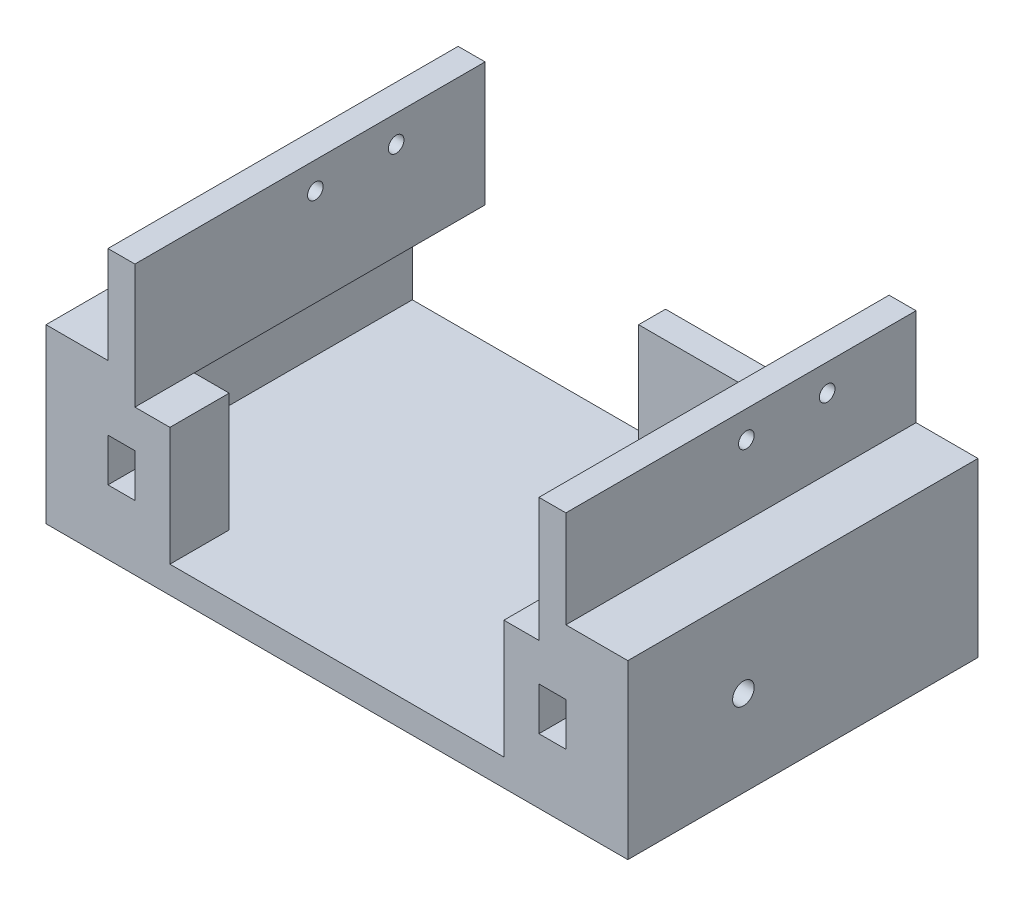
SolidWorks part; units mm, degrees
ref_plane "前基準面" through (0, 0, 0) normal (0, 0, 1) x (1, 0, 0)
ref_plane "上基準面" through (0, 0, 0) normal (0, 1, 0) x (1, 0, 0)
ref_plane "右基準面" through (0, 0, 0) normal (1, 0, 0) x (0, 0, -1)
sketch "草圖1" plane through (0, 0, 0) normal (0, 0, 1) x (1, 0, 0)
  line L0 (-26.3644, 0.7783) -> (-21.3644, 0.7783)
  line L1 (-21.3644, 0.7783) -> (-21.3644, -22.2217)
  line L2 (-21.3644, -22.2217) -> (-34.8644, -22.2217)
  line L3 (-34.8644, -22.2217) -> (-34.8644, -44.2217)
  line L4 (-34.8644, -44.2217) -> (67.1356, -44.2217)
  line L5 (67.1356, -44.2217) -> (67.1356, -22.2217)
  line L6 (67.1356, -22.2217) -> (53.6356, -22.2217)
  line L7 (53.6356, -22.2217) -> (53.6356, 0.7783)
  line L8 (53.6356, 0.7783) -> (58.6356, 0.7783)
  line L9 (58.6356, 0.7783) -> (58.6356, -17.2217)
  line L10 (58.6356, -17.2217) -> (70.1356, -17.2217)
  line L11 (70.1356, -17.2217) -> (70.1356, -49.2217)
  line L12 (70.1356, -49.2217) -> (-37.8644, -49.2217)
  line L13 (-37.8644, -49.2217) -> (-37.8644, -17.2217)
  line L14 (-37.8644, -17.2217) -> (-26.3644, -17.2217)
  line L15 (-26.3644, -17.2217) -> (-26.3644, 0.7783)
  dimension "D1" = 5
  dimension "D2" = 3
  dimension "D3" = 3
  dimension "D4" = 5
  dimension "D5" = 5
  dimension "D6" = 22
  dimension "D7" = 22
  dimension "D8" = 5
  dimension "D9" = 5
  dimension "D10" = 102
  dimension "D11" = 75
  dimension "D12" = 13.5
  dimension "D13" = 45
  dimension "D14" = 45
extrude "填料-伸長1" add sketch "草圖1" along normal blind 65
sketch "草圖3" plane through (-37.8644, 0, 0) normal (-1, 0, 0) x (0, 0, 1)
  line L0 (65, -17.2217) -> (0, -17.2217) construction
  circle A0 centre (43.5457, -33.2217) radius 2
  dimension "D2" = 4
  dimension "D1" = 16
extrude "除料-伸長2" cut sketch "草圖3" against normal through all contours A0
sketch "草圖4" plane through (0, 0, 0) normal (0, 0, -1) x (-1, 0, 0)
  line L0 (-67.1356, -44.2217) -> (34.8644, -44.2217) construction
  line L1 (-42.1356, -44.2217) -> (-12.1356, -44.2217)
  line L2 (-42.1356, -44.2217) -> (-42.1356, -22.2217)
  line L3 (-42.1356, -22.2217) -> (-12.1356, -22.2217)
  line L4 (-12.1356, -44.2217) -> (-12.1356, -22.2217)
  line L5 (-67.1356, -22.2217) -> (-67.1356, -44.2217) construction
  dimension "D1" = 30
  dimension "D2" = 25
  dimension "D3" = 22
extrude "填料-伸長2" add sketch "草圖4" against normal blind 5
sketch "草圖9" plane through (-21.3644, 0, 0) normal (1, 0, 0) x (0, 0, -1)
  circle A0 centre (-31.5, -4.2217) radius 1.45
  circle A1 centre (-16.5, -4.2217) radius 1.45
extrude "除料-伸長4" cut sketch "草圖9" against normal through all and the other way through all
sketch "草圖10" plane through (0, 0, 65) normal (0, 0, 1) x (1, 0, 0)
  line L1 (-34.8644, -44.2217) -> (-14.8644, -44.2217)
  line L2 (-34.8644, -44.2217) -> (-34.8644, -22.2217)
  line L3 (-34.8644, -22.2217) -> (-14.8644, -22.2217)
  line L4 (-14.8644, -44.2217) -> (-14.8644, -22.2217)
  line L5 (67.1356, -44.2217) -> (-34.8644, -44.2217) construction
  line L7 (67.1356, -22.2217) -> (47.1356, -22.2217)
  line L8 (67.1356, -22.2217) -> (67.1356, -44.2217)
  line L9 (67.1356, -44.2217) -> (47.1356, -44.2217)
  line L10 (47.1356, -22.2217) -> (47.1356, -44.2217)
  line L11 (-26.3644, -29.2217) -> (-21.3644, -29.2217)
  line L12 (-26.3644, -29.2217) -> (-26.3644, -37.2217)
  line L13 (-26.3644, -37.2217) -> (-21.3644, -37.2217)
  line L14 (-21.3644, -29.2217) -> (-21.3644, -37.2217)
  line L15 (53.6356, -29.2217) -> (58.6356, -29.2217)
  line L16 (53.6356, -29.2217) -> (53.6356, -37.2217)
  line L17 (53.6356, -37.2217) -> (58.6356, -37.2217)
  line L18 (58.6356, -29.2217) -> (58.6356, -37.2217)
  line M53 (67.1356, -44.2217) -> (-34.8644, -44.2217)
  line M55 (53.6356, -22.2217) -> (67.1356, -22.2217)
  line M56 (67.1356, -22.2217) -> (67.1356, -44.2217)
  dimension "D1" = 20
  dimension "D2" = 20
  dimension "D3" = 22
  dimension "D4" = 8
  dimension "D5" = 5
  dimension "D6" = 8.5
  dimension "D7" = 7
  dimension "D8" = 5
  dimension "D9" = 8
  dimension "D10" = 8.5
  dimension "D11" = 7
extrude "填料-伸長6" add sketch "草圖10" against normal blind 11 contours L7 L10 L15 L18 L17 L16 M53 M56 M55 | L3 L4 L1 L2 | L13 L14 L11 L12
